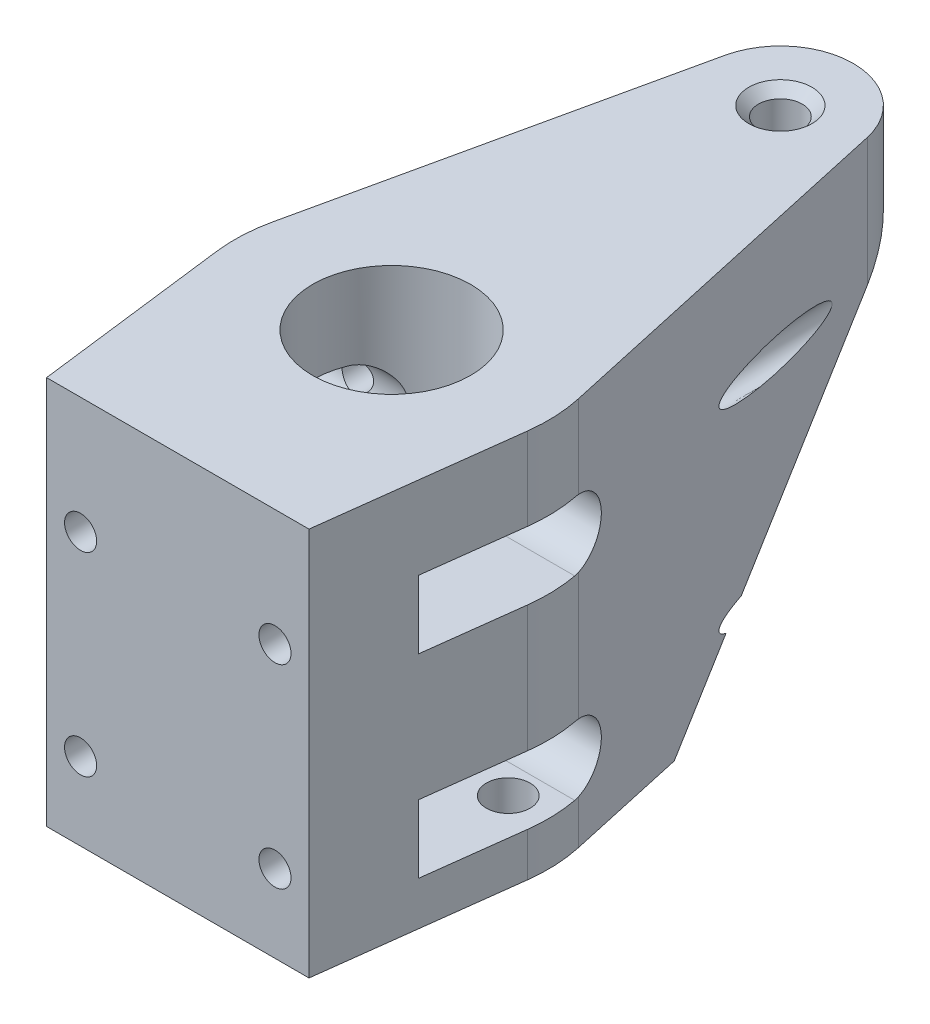
SolidWorks part; units mm, degrees
material "PET"
ref_plane "Front Plane" through (0, 0, 0) normal (0, 0, 1) x (1, 0, 0)
ref_plane "Top Plane" through (0, 0, 0) normal (0, 1, 0) x (1, 0, 0)
ref_plane "Right Plane" through (0, 0, 0) normal (1, 0, 0) x (0, 0, -1)
sketch "Sketch1" plane through (0, 0, 0) normal (0, 1, 0) x (1, 0, 0)
  line L0 (0, 0) -> (0, 98.125) construction
  line L1 (-7.3236, 63.6172) -> (-15.7457, 25.477)
  line L2 (7.3236, 63.6172) -> (15.7457, 25.477)
  line L3 (-13.5, 0) -> (13.5, 0)
  line L4 (-13.5, 0) -> (-16.0004, 19.9996)
  line L5 (13.5, 0) -> (16.0004, 19.9996)
  arc A0 (-15.7457, 25.477) -> (-16.0004, 19.9996) centre (0, 22) ccw
  circle A1 centre (0, 62) radius 2.25
  arc A2 (7.3236, 63.6172) -> (-7.3236, 63.6172) centre (0, 62) ccw
  circle A3 centre (0, 22) radius 8.125
  arc A4 (16.0004, 19.9996) -> (15.7457, 25.477) centre (0, 22) ccw
  dimension "D1" = 32.25
  dimension "D2" = 22
  dimension "D3" = 4.5
  dimension "D4" = 40
  dimension "D5" = 15
  dimension "D7" = 16.25
  dimension "D6" = 27
extrude "Boss-Extrude1" add sketch "Sketch1" along normal blind 44
sketch "Sketch2" plane through (0, 0, 0) normal (0, -1, 0) x (1, 0, 0)
  line L0 (-15.7457, -25.477) -> (-12.9527, -38.125)
  line L2 (15.7457, -25.477) -> (12.9527, -38.125)
  line L4 (12.9527, -38.125) -> (-12.9527, -38.125)
  line L5 (-13.5, 0) -> (13.5, 0)
  line L6 (13.5, 0) -> (16.0004, -19.9996)
  line L7 (-13.5, 0) -> (-16.0004, -19.9996)
  arc A0 (15.7457, -25.477) -> (16.0004, -19.9996) centre (0, -22) ccw
  arc A1 (-16.0004, -19.9996) -> (-15.7457, -25.477) centre (0, -22) ccw
extrude "Cut-Extrude1" cut sketch "Sketch2" against normal blind 4
sketch "Sketch3" plane through (0, 0, 0) normal (1, 0, 0) x (0, 0, -1)
  line L1 (69.5, 0) -> (69.5, 44) construction
  line L2 (69.5, 37) -> (69.5, 0)
  line L3 (69.5, 0) -> (38.125, 0)
  line L4 (69.5, 44) -> (63.6172, 44) construction
  line L5 (38.125, 0) -> (38.125, 4)
  line L6 (38.125, 4) -> (69.5, 37)
  dimension "D1" = 7
extrude "Cut-Extrude3" cut sketch "Sketch3" against normal through all both and the other way through all
sketch "Sketch4" plane through (0, 4, 0) normal (0, -1, 0) x (1, 0, 0)
  circle A0 centre (0, -22) radius 12 construction
  point P3 (0, -10)
  point P4 (0, -34)
  point P5 (12, -22)
  point P6 (-12, -22)
  dimension "D1" = 24
hole_wizard "Ø4.5 (4.5) Diameter Hole1" positions "Sketch5" profile "Sketch6" hole size "Ø4.5" standard "ANSI Metric"
sketch "Sketch5" plane through (0, 4, 0) normal (0, -1, 0) x (-1, 0, 0)
  point P0 (12, 22)
  point P3 (0, 34)
  point P6 (-12, 22)
  point P9 (0, 10)
sketch "Sketch6" plane through (-12, 4, -22) normal (1, 0, 0) x (0, 0, -1)
  line L0 (0, 0) -> (0, 11.3519)
  line L1 (0, 11.3519) -> (2.25, 10)
  line L2 (2.25, 10) -> (2.25, 0)
  line L5 (2.25, 0) -> (0, 0)
  line L10 (0, 11.3519) -> (-2.25, 10) construction
  line L11 (0, -6.35) -> (0, 107.95) construction
  dimension "Hole Dia." = 4.5
  dimension "Hole Depth" = 10
  dimension "Drill Angle" = 118
sketch "Sketch7" plane through (0, 0, 0) normal (0, 0, 1) x (1, 0, 0)
  line L0 (0, 44) -> (0, 0) construction
  line L1 (-13.5, 44) -> (13.5, 44) construction
  line L3 (-10, 32) -> (10, 32)
  line L4 (-10, 32) -> (-10, 12)
  line L5 (-10, 12) -> (10, 12)
  line L6 (10, 32) -> (10, 12)
  line L7 (-10, 32) -> (10, 12) construction
  line L8 (-10, 12) -> (10, 32) construction
  point P5 (0, 22)
  dimension "D1" = 22
  dimension "D2" = 20
  dimension "D3" = 20
hole_wizard "Ø3.3 (3.3) Diameter Hole1" positions "Sketch8" profile "Sketch9" hole size "Ø3.3" standard "ANSI Metric" end condition through all
sketch "Sketch8" plane through (0, 0, 0) normal (0, 0, 1) x (1, 0, 0)
  point P0 (-10, 32)
  point P3 (10, 32)
  point P6 (10, 12)
  point P9 (-10, 12)
sketch "Sketch9" plane through (-10, 32, 0) normal (1, 0, 0) x (0, -1, 0)
  line L0 (0, 0) -> (0, 69.5)
  line L1 (0, 69.5) -> (1.65, 69.5)
  line L2 (1.65, 69.5) -> (1.65, 0)
  line L5 (1.65, 0) -> (0, 0)
  line L11 (0, -6.35) -> (0, 107.95) construction
  dimension "Thru Hole Dia." = 3.3
  dimension "Thru Hole Depth" = 69.5
sketch "Sketch10" plane through (0, 0, 0) normal (1, 0, 0) x (0, 0, -1)
  line L0 (0, 44) -> (0, 0) construction
  line L1 (10, 35.5) -> (25, 35.5)
  line L2 (10, 35.5) -> (10, 28.5)
  line L3 (10, 28.5) -> (25, 28.5)
  line L5 (10, 15.5) -> (25, 15.5)
  line L6 (10, 15.5) -> (10, 8.5)
  line L7 (10, 8.5) -> (25, 8.5)
  line L9 (0, 32) -> (0, 12) construction
  line L11 (0, 22) -> (58.0636, 22) construction
  line L12 (10, 32) -> (25, 32) construction
  line L13 (10, 12) -> (25, 12) construction
  arc A0 (25, 8.5) -> (25, 15.5) centre (25, 12) ccw
  arc A1 (25, 28.5) -> (25, 35.5) centre (25, 32) ccw
  dimension "D1" = 7
  dimension "D2" = 15
  dimension "D3" = 10
  dimension "D4" = 10
  dimension "D5" = 7
  dimension "D6" = 15
  dimension "D7" = 10
  dimension "D8" = 10
extrude "Cut-Extrude4" cut sketch "Sketch10" against normal through all both and the other way through all
chamfer "Chamfer1" distance 1 angle 45 5 edges at (-12, 4, -24.25) (0, 4, -36.25) (12, 4, -24.25) (0, 4, -12.25) (0, 44, -59.75)
